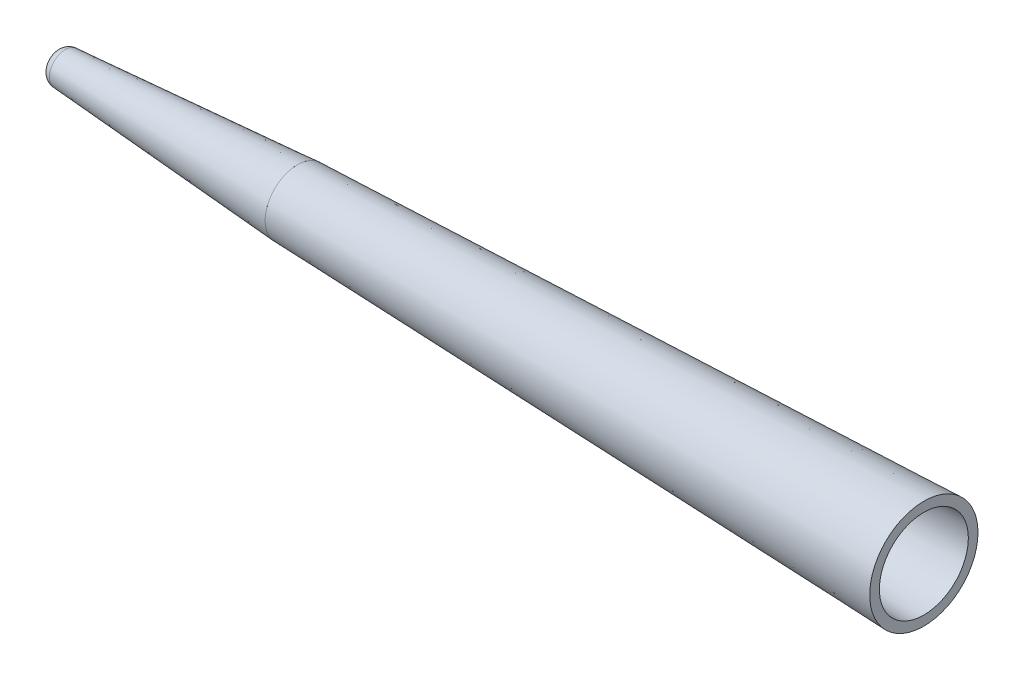
SolidWorks part; units mm, degrees
ref_plane "Front Plane" through (0, 0, 0) normal (0, 0, 1) x (1, 0, 0)
ref_plane "Top Plane" through (0, 0, 0) normal (0, 1, 0) x (1, 0, 0)
ref_plane "Right Plane" through (0, 0, 0) normal (1, 0, 0) x (0, 0, -1)
sketch "Sketch2" plane through (0, 0, 0) normal (0, 0, 1) x (1, 0, 0)
  line L0 (-19.2758, 0) -> (50, 0) construction
  line L1 (0, 21.4747) -> (0, -15.9358) construction
  line L2 (0, 1.2) -> (54.9325, 5.0413) construction
  line L3 (0, 3.2) -> (55.9028, 7.1091) construction
  line L4 (0, 1.2) -> (50, 4.6963)
  line L5 (1.8511, 3.3294) -> (50, 6.6963)
  line L6 (50, 0) -> (50, 20.2328) construction
  line L7 (50, 6.6963) -> (50, 4.6963)
  arc A0 (0, 1.2) -> (1.8511, 3.3294) centre (1.9903, 1.3392) cw
  dimension "D1" = 4
  dimension "D2" = 1.2
  dimension "D3" = 2
  dimension "D4" = 50
revolve "Revolve2" add sketch "Sketch2" angle 360 about L0
ref_plane "Plane1" through (50, 0, 0) normal (1, 0, 0) x (0, 0, -1)
ref_axis "Axis1" through (50, 0, 0) along (-1, 0, 0)
sketch "Sketch3" plane through (0, 0, 0) normal (0, 0, 1) x (1, 0, 0)
  line L0 (50, 6.6963) -> (180, 6.6963) construction
  line L1 (50, -7.366) -> (50, 7.366) construction
  line L2 (50, 6.6963) -> (1.8511, 3.3294) construction
  line L3 (50, 6.6963) -> (180, 11.236) construction
  line L4 (50, 4.6951) -> (180, 9.2348)
  line L5 (180, 9.2348) -> (180, 11.236)
  line L6 (180, 11.236) -> (50, 6.6963)
  line L7 (50, 6.6963) -> (50, 4.6951)
  dimension "D1" = 2
  dimension "D2" = 130
  dimension "D3" = 2
revolve "Revolve3" add sketch "Sketch3" angle 360 about axis through (50, 0, 0) along (-1, 0, 0)
sketch "Sketch4" plane through (0, 0, 0) normal (0, 0, 1) x (1, 0, 0)
  line L0 (50, 6.6963) -> (47.323, 6.6963) construction
  line L3 (50, 5.1963) -> (42.8414, 5.1963) construction
  line L4 (50, 6.1951) -> (47, 5.4841)
  line L5 (47, 5.4841) -> (50, 5.1963)
  line L6 (50, 6.1951) -> (50, 5.1963)
  line L7 (50, 6.6963) -> (1.8511, 3.3294) construction
  line L8 (50, -7.366) -> (50, 7.366) construction
  dimension "D1" = 1.5
  dimension "D2" = 3
  dimension "D3" = 1
  dimension "D4" = 0.5
